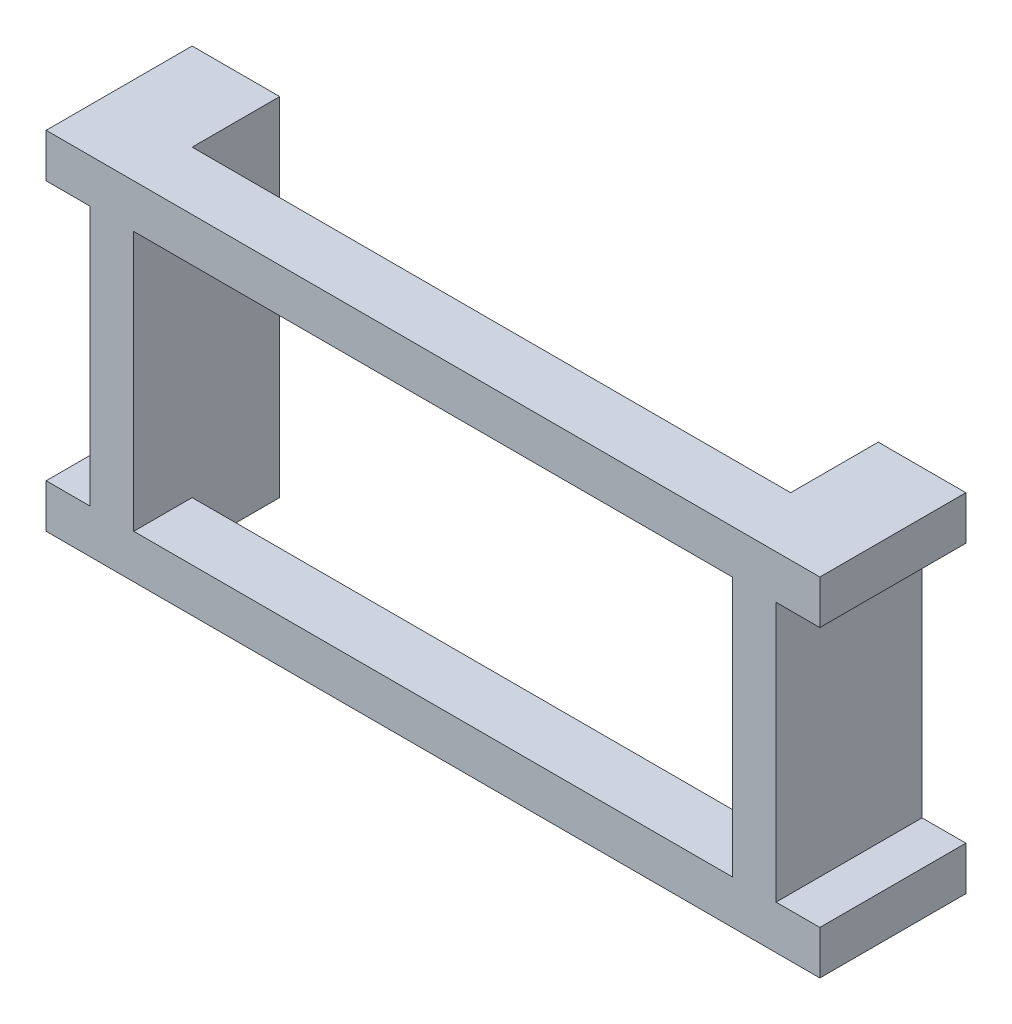
SolidWorks part; units mm, degrees
material "1060 Alloy"
ref_plane "Front Plane" through (0, 0, 0) normal (0, 0, 1) x (1, 0, 0)
ref_plane "Top Plane" through (0, 0, 0) normal (0, 1, 0) x (1, 0, 0)
ref_plane "Right Plane" through (0, 0, 0) normal (1, 0, 0) x (0, 0, -1)
sketch "Sketch1" plane through (0, 0, 0) normal (0, 0, 1) x (1, 0, 0)
  line L0 (12.2817, 9.552) -> (15.2817, 9.552)
  line L1 (-37.7183, 12.552) -> (15.2817, 12.552)
  line L2 (-37.7183, 12.552) -> (-37.7183, 9.552)
  line L3 (15.2817, 9.552) -> (15.2817, 12.552)
  line L4 (-34.7183, 9.552) -> (-34.7183, -8.238)
  line L5 (-31.7183, 9.552) -> (-31.7183, -8.238)
  line L6 (-37.7183, -8.238) -> (-37.7183, -11.238)
  line L7 (-37.7183, -11.238) -> (15.2817, -11.238)
  line L8 (12.2817, 9.552) -> (12.2817, -8.238)
  line L9 (-31.7183, -8.238) -> (9.2817, -8.238)
  line L10 (15.2817, -8.238) -> (15.2817, -11.238)
  line L11 (15.2817, -8.238) -> (12.2817, -8.238)
  line L12 (9.2817, 9.552) -> (9.2817, -8.238)
  line L13 (-31.7183, 9.552) -> (9.2817, 9.552)
  line L15 (-37.7183, 9.552) -> (-34.7183, 9.552)
  line L21 (-37.7183, -8.238) -> (-34.7183, -8.238)
  dimension "D1" = 3
  dimension "D2" = 3
  dimension "D3" = 47
  dimension "D4" = 3
  dimension "D5" = 3
extrude "Boss-Extrude1" add sketch "Sketch1" along normal blind 10
hole_wizard "M2.5x0.45 Tapped Hole2" [suppressed] positions "Sketch4" profile "Sketch5" tap size "M2.5x0.45" standard "Ansi Metric"
sketch "Sketch4" plane through (-34.7183, 0, 0) normal (-1, 0, 0) x (0, 0, 1)
  line L0 (10, 12.552) -> (0, 12.552) construction
  line L2 (0, 9.552) -> (0, -8.238) construction
  line L3 (10, -11.238) -> (0, -11.238) construction
  point P0 (5, 4.552)
  point P1 (5, -3.238)
  dimension "D1" = 8
  dimension "D2" = 8
  dimension "D3" = 5
  dimension "D4" = 5
sketch "Sketch5" plane through (-34.7183, 4.552, 5) normal (0, 1, 0) x (0, 0, 1)
  line L0 (0, 0) -> (0, 7.8659)
  line L1 (0, 7.8659) -> (1.025, 7.25)
  line L2 (1.025, 7.25) -> (1.025, 0)
  line L5 (1.025, 0) -> (0, 0)
  line L10 (0, 7.8659) -> (-1.025, 7.25) construction
  line L11 (0, -6.35) -> (0, 107.95) construction
  dimension "Tap Drill Dia." = 2.05
  dimension "Tap Drill Depth" = 7.25
  dimension "Drill Angle" = 118
cosmetic thread "Hole Thread1" [suppressed] parameters "D1"=3, "D2"=2.5
cosmetic thread "Hole Thread2" [suppressed] parameters "D1"=3, "D2"=2.5
hole_wizard "M2.5x0.45 Tapped Hole1" [suppressed] positions "Sketch7" profile "Sketch6" tap size "M2.5x0.45" standard "Ansi Metric"
sketch "Sketch7" plane through (12.2817, 2.4767, 1.6069) normal (1, 0, 0) x (0, 0, -1)
  line L3 (-8.3931, 10.0753) -> (1.6069, 10.0753) construction
  line L4 (-8.3931, -13.7147) -> (1.6069, -13.7147) construction
  line L5 (-8.3931, 7.0753) -> (-8.3931, 10.0753) construction
  line L6 (-8.3931, -13.7147) -> (-8.3931, -10.7147) construction
  point P0 (-3.3931, 2.0753)
  point P1 (-3.3931, -5.7147)
  dimension "D1" = 8
  dimension "D2" = 8
  dimension "D3" = 5
  dimension "D4" = 5
sketch "Sketch6" plane through (12.2817, 4.552, 5) normal (0, 1, 0) x (0, 0, -1)
  line L0 (0, 0) -> (0, 7.8659)
  line L1 (0, 7.8659) -> (1.025, 7.25)
  line L2 (1.025, 7.25) -> (1.025, 0)
  line L5 (1.025, 0) -> (0, 0)
  line L10 (0, 7.8659) -> (-1.025, 7.25) construction
  line L11 (0, -6.35) -> (0, 107.95) construction
  dimension "Tap Drill Dia." = 2.05
  dimension "Tap Drill Depth" = 7.25
  dimension "Drill Angle" = 118
cosmetic thread "Hole Thread3" [suppressed] parameters "D1"=3, "D2"=2.5
cosmetic thread "Hole Thread4" [suppressed] parameters "D1"=3, "D2"=2.5
sketch "Sketch10" plane through (0, 0, 0) normal (0, 0, -1) x (-1, 0, 0)
  line L0 (37.7183, -11.238) -> (-15.2817, -11.238) construction
  line L1 (31.7183, -8.238) -> (-9.2817, -8.238)
  line L2 (31.7183, -8.238) -> (31.7183, -11.238)
  line L3 (31.7183, -11.238) -> (-9.2817, -11.238)
  line L4 (-9.2817, -8.238) -> (-9.2817, -11.238)
extrude "Cut-Extrude1" cut sketch "Sketch10" against normal blind 6
ref_plane "Plane1" through (0, 0.657, 0) normal (0, 1, 0) x (1, 0, 0)
ref_plane "Plane2" through (0, 0, 5) normal (0, 0, 1) x (1, 0, 0)
mirror "Mirror3" about plane through (0, 0.657, 0) normal (0, 1, 0) of "Cut-Extrude1"
